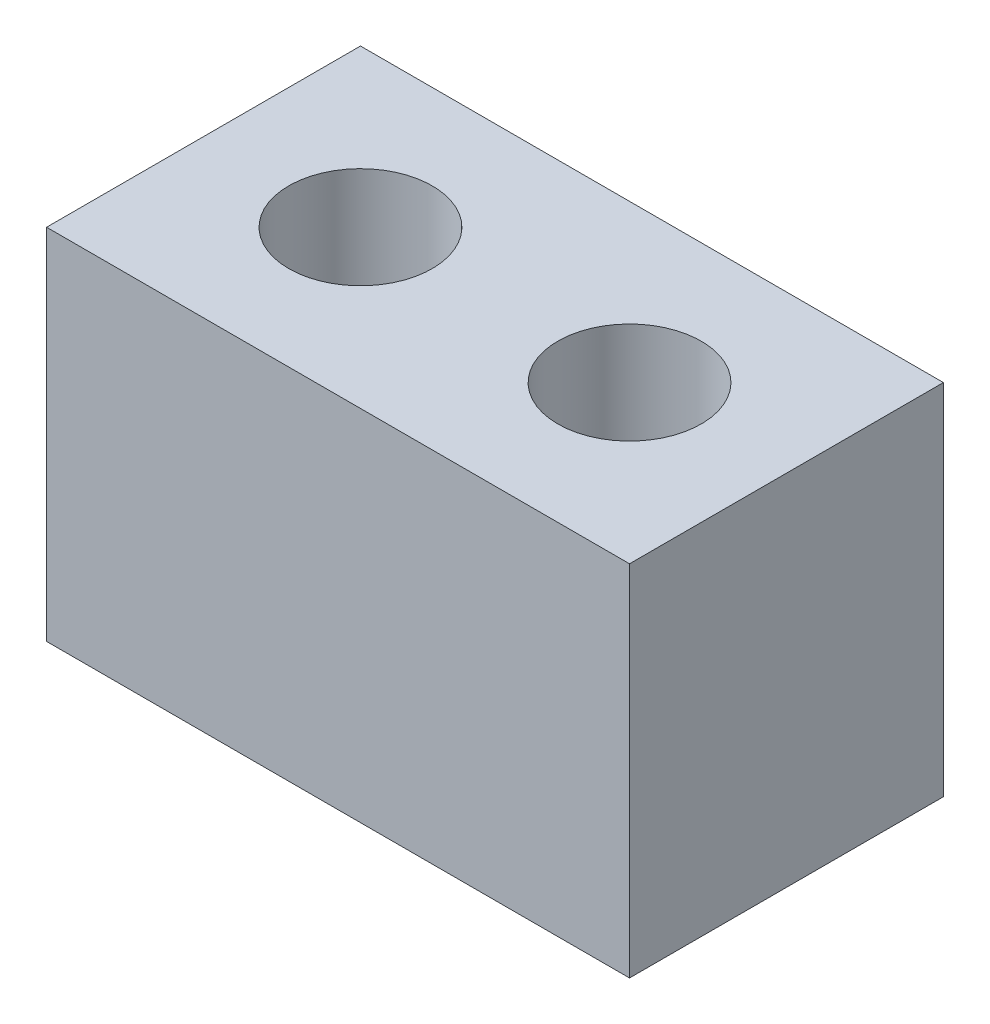
SolidWorks part; units mm, degrees
ref_plane "Front Plane" through (0, 0, 0) normal (0, 0, 1) x (1, 0, 0)
ref_plane "Top Plane" through (0, 0, 0) normal (0, 1, 0) x (1, 0, 0)
ref_plane "Right Plane" through (0, 0, 0) normal (1, 0, 0) x (0, 0, -1)
sketch "Sketch2" plane through (0, 0, 0) normal (0, 1, 0) x (1, 0, 0)
  line L0 (-3, 0) -> (3, 0) construction
  line L1 (-6.5, 3.5) -> (6.5, 3.5)
  line L2 (-6.5, 3.5) -> (-6.5, -3.5)
  line L3 (-6.5, -3.5) -> (6.5, -3.5)
  line L4 (6.5, 3.5) -> (6.5, -3.5)
  line L5 (-6.5, 3.5) -> (6.5, -3.5) construction
  line L6 (-6.5, -3.5) -> (6.5, 3.5) construction
  circle A0 centre (-3, 0) radius 1.6
  circle A1 centre (3, 0) radius 1.6
  point P0 (0, 0)
  dimension "D2" = 3.2
  dimension "D3" = 3.2
  dimension "D1" = 7
  dimension "D4" = 13
  dimension "D5" = 6
extrude "Boss-Extrude1" add sketch "Sketch2" along normal blind 8
